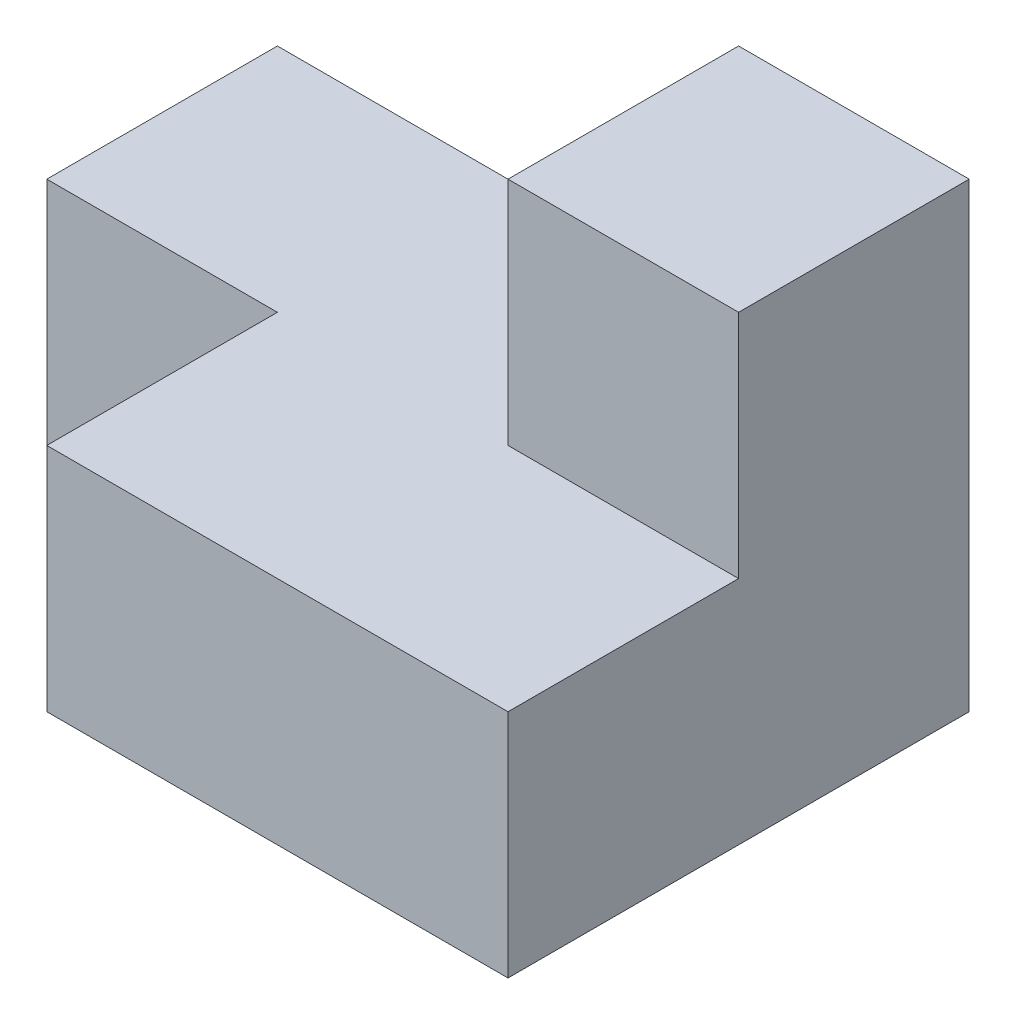
SolidWorks part; units mm, degrees
ref_plane "Plano frontal" through (0, 0, 0) normal (0, 0, 1) x (1, 0, 0)
ref_plane "Plano superior" through (0, 0, 0) normal (0, 1, 0) x (1, 0, 0)
ref_plane "Plano direito" through (0, 0, 0) normal (1, 0, 0) x (0, 0, -1)
sketch "Esboço1" plane through (0, 0, 0) normal (0, 0, 1) x (1, 0, 0)
  line L1 (0, 0) -> (60, 0)
  line L2 (0, 0) -> (0, 20)
  line L3 (0, 20) -> (60, 20)
  line L4 (60, 0) -> (60, 20)
  dimension "D1" = 60
  dimension "D2" = 20
extrude "Ressalto-extrusão1" add sketch "Esboço1" along normal blind 20
sketch "Esboço2" plane through (0, 0, 20) normal (0, 0, 1) x (1, 0, 0)
  line L0 (60, 20) -> (0, 20) construction
  line L1 (60, 0) -> (20, 0)
  line L2 (60, 0) -> (60, 20)
  line L3 (60, 20) -> (20, 20)
  line L4 (20, 0) -> (20, 20)
  dimension "D1" = 40
extrude "Ressalto-extrusão2" add sketch "Esboço2" along normal blind 20
sketch "Esboço3" plane through (0, 20, 0) normal (0, 1, 0) x (1, 0, 0)
  line L1 (60, 0) -> (40, 0)
  line L2 (60, 0) -> (60, -20)
  line L3 (60, -20) -> (40, -20)
  line L4 (40, 0) -> (40, -20)
  dimension "D1" = 20
  dimension "D2" = 20
extrude "Ressalto-extrusão3" add sketch "Esboço3" along normal blind 20
